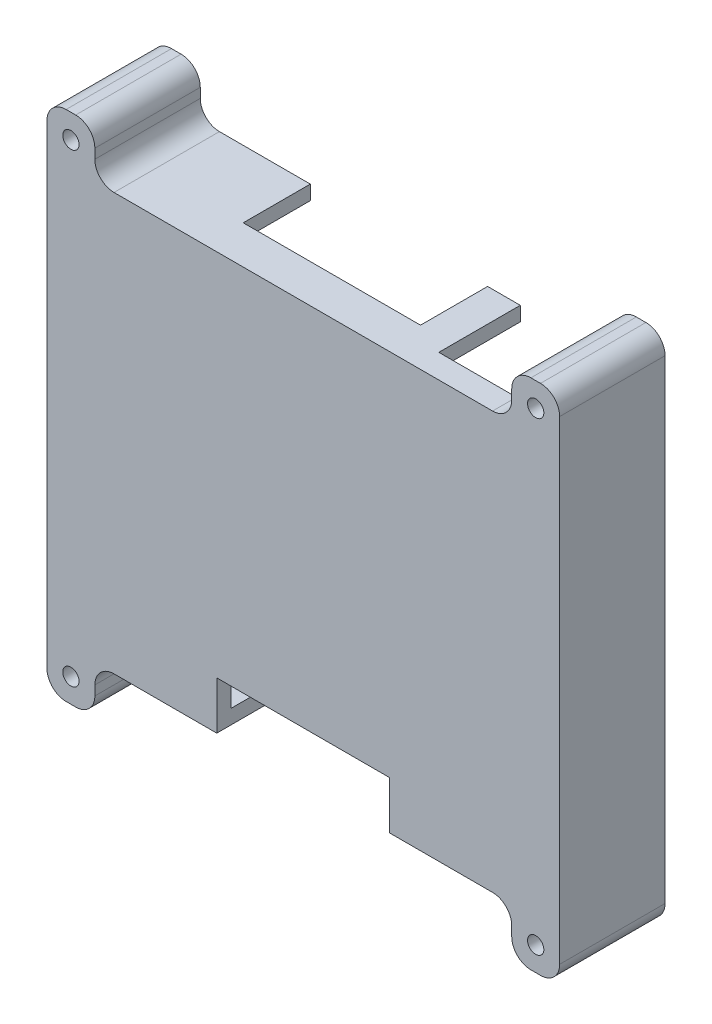
SolidWorks part; units mm, degrees
ref_plane "Płaszczyzna przednia" through (0, 0, 0) normal (0, 0, 1) x (1, 0, 0)
ref_plane "Płaszczyzna górna" through (0, 0, 0) normal (0, 1, 0) x (1, 0, 0)
ref_plane "Płaszczyzna prawa" through (0, 0, 0) normal (1, 0, 0) x (0, 0, -1)
sketch "Sketch1" plane through (0, 0, 0) normal (0, 0, 1) x (1, 0, 0)
  line L1 (-53.5, 43.5) -> (53.5, 43.5)
  line L2 (-53.5, 43.5) -> (-53.5, -43.5)
  line L3 (-53.5, -43.5) -> (53.5, -43.5)
  line L4 (53.5, 43.5) -> (53.5, -43.5)
  line L5 (0, -43.5) -> (0, 43.5) construction
  line L6 (-53.5, 0) -> (53.5, 0) construction
  point P92 (0, 0)
  dimension "D1" = 107
  dimension "D2" = 87
extrude "Boss-Extrude1" add sketch "Sketch1" along normal blind 22
sketch "Sketch2" plane through (0, 0, 0) normal (0, 0, -1) x (-1, 0, 0)
  line L1 (-53.5, -43.5) -> (-43.5, -43.5)
  line L2 (-53.5, -43.5) -> (-53.5, -53.5)
  line L3 (-53.5, -53.5) -> (-43.5, -53.5)
  line L4 (-43.5, -43.5) -> (-43.5, -53.5)
  line L5 (-48.5, -53.5) -> (-48.5, -43.5) construction
  line L6 (-53.5, -48.5) -> (-43.5, -48.5) construction
  point P252 (-48.5, -48.5)
  dimension "D1" = 10
  dimension "D2" = 10
extrude "Boss-Extrude2" add sketch "Sketch2" against normal up to surface (22 mm away) up to face at (0, 0, 22)
mirror "Mirror1" about plane through (0, 0, 0) normal (0, 1, 0) of "Boss-Extrude2" second plane through (0, 0, 0) second plane normal (1, 0, 0)
sketch "Sketch3" plane through (0, 0, 0) normal (0, 0, -1) x (-1, 0, 0)
  line L0 (-43.5, 43.5) -> (43.5, 43.5) construction
  line L1 (-50.5, 40.5) -> (50.5, 40.5)
  line L2 (-50.5, 40.5) -> (-50.5, -40.5)
  line L3 (-50.5, -40.5) -> (50.5, -40.5)
  line L4 (50.5, 40.5) -> (50.5, -40.5)
  line L5 (0, -40.5) -> (0, 40.5) construction
  line L6 (-50.5, 0) -> (50.5, 0) construction
  line L7 (-53.5, -53.5) -> (-53.5, 53.5) construction
  point P200 (0, 0)
  dimension "D1" = 3
  dimension "D2" = 3
extrude "Cut-Extrude1" cut sketch "Sketch3" against normal offset from surface (19 mm away) 3 up to face at (0, 0, 22)
sketch "Sketch4" plane through (0, 0, 22) normal (0, 0, 1) x (1, 0, 0)
  line L1 (-53.5, -53.5) -> (-43.5, -53.5)
  line L2 (-53.5, -53.5) -> (-53.5, -43.5)
  line L3 (-53.5, -43.5) -> (-43.5, -43.5)
  line L4 (-43.5, -53.5) -> (-43.5, -43.5)
  line L5 (-48.5, -43.5) -> (-48.5, -53.5) construction
  line L6 (-53.5, -48.5) -> (-43.5, -48.5) construction
  line L7 (0, -55) -> (0, 55) construction
  line L8 (53.5, -43.5) -> (43.5, -43.5)
  line L9 (43.5, -53.5) -> (43.5, -43.5)
  line L10 (53.5, -53.5) -> (43.5, -53.5)
  line L11 (53.5, -53.5) -> (53.5, -43.5)
  line L12 (53.5, -48.5) -> (43.5, -48.5) construction
  line L13 (48.5, -43.5) -> (48.5, -53.5) construction
  line L14 (55, 0) -> (-55, 0) construction
  point P12 (48.5, -48.5)
  point P17 (48.5, 48.5)
  point P18 (-48.5, 48.5)
  point P160 (-48.5, -48.5)
hole_wizard "M3 Clearance Hole1" positions "Sketch4" profile "Sketch5" hole size "M3" standard "DIN" end condition up to next
sketch "Sketch5" plane through (-48.5, -48.5, 22) normal (1, 0, 0) x (0, -1, 0)
  line L0 (0, 0) -> (0, 22)
  line L1 (0, 22) -> (1.7, 22)
  line L2 (1.7, 22) -> (1.7, 0)
  line L5 (1.7, 0) -> (0, 0)
  line L11 (0, -6.35) -> (0, 107.95) construction
  dimension "Thru Hole Dia." = 3.4
  dimension "Thru Hole Depth" = 22
sketch "Sketch6" plane through (0, -43.5, 0) normal (0, -1, 0) x (1, 0, 0)
  line L0 (-43.5, 0) -> (43.5, 0) construction
  line L1 (40.285, 0) -> (24.285, 0)
  line L2 (40.285, 0) -> (40.285, 17)
  line L3 (40.285, 17) -> (24.285, 17)
  line L4 (24.285, 0) -> (24.285, 17)
  line L5 (32.285, 17) -> (32.285, 0) construction
  line L6 (40.285, 8.5) -> (24.285, 8.5) construction
  line L8 (24.735, 14.9914) -> (39.835, 14.9914) construction
  point P8 (32.285, 14.9914)
  point P196 (32.285, 8.5)
  dimension "D1" = 17
  dimension "D2" = 16
  dimension "D3" = 2.0086
extrude "Cut-Extrude2" cut sketch "Sketch6" against normal up to next
sketch "Sketch12" plane through (0, 43.5, 0) normal (0, 1, 0) x (1, 0, 0)
  line L0 (39.285, -17) -> (23.285, -17)
  line L1 (39.285, -17) -> (39.285, 0)
  line L2 (39.285, 0) -> (23.285, 0)
  line L3 (23.285, -17) -> (23.285, 0)
  line L4 (31.285, 0) -> (31.285, -17) construction
  line L5 (39.285, -8.5) -> (23.285, -8.5) construction
  line L6 (43.5, 0) -> (-43.5, 0) construction
  line L7 (23.735, -14.9914) -> (38.835, -14.9914) construction
  point P4 (31.285, -5.5826)
  point P9 (31.285, -8.5)
  point P13 (31.285, -14.9914)
  dimension "D1" = 17
  dimension "D2" = 16
extrude "Cut-Extrude6" cut sketch "Sketch12" against normal up to next
sketch "Sketch8" plane through (0, 43.5, 0) normal (0, 1, 0) x (1, 0, 0)
  line L0 (23.285, 0) -> (-43.5, 0) construction
  line L1 (-20.536, 0) -> (16.464, 0)
  line L2 (-20.536, 0) -> (-20.536, -14)
  line L3 (-20.536, -14) -> (16.464, -14)
  line L4 (16.464, 0) -> (16.464, -14)
  line L5 (-2.036, -14) -> (-2.036, 0) construction
  line L6 (-20.536, -7) -> (16.464, -7) construction
  line L7 (-0.131, -1.5914) -> (1.139, -1.5914) construction
  line L8 (-3.941, -1.5914) -> (-0.131, -1.5914) construction
  line L9 (-5.211, -1.5914) -> (-3.941, -1.5914) construction
  line L10 (-0.131, -1.5914) -> (1.139, -1.5914) construction
  line L11 (-5.211, -1.5914) -> (-3.941, -1.5914) construction
  point P11 (-0.131, -1.5914)
  point P12 (-3.941, -1.5914)
  point P13 (-2.036, -1.5914)
  point P60 (-2.036, -7)
  dimension "D1" = 37
  dimension "D2" = 14
  dimension "D3" = 1.27
extrude "Cut-Extrude3" cut sketch "Sketch8" against normal up to next
sketch "Sketch9" plane through (0, 0, 22) normal (0, 0, 1) x (1, 0, 0)
  line L0 (-43.5, -43.5) -> (43.5, -43.5) construction
  line L1 (17.9441, -43.5) -> (-18.0559, -43.5)
  line L2 (17.9441, -43.5) -> (17.9441, -33.5)
  line L3 (17.9441, -33.5) -> (-18.0559, -33.5)
  line L4 (-18.0559, -43.5) -> (-18.0559, -33.5)
  line L5 (-0.0559, -33.5) -> (-0.0559, -43.5) construction
  line L6 (17.9441, -38.5) -> (-18.0559, -38.5) construction
  line L8 (15.1941, -33.8779) -> (-15.3059, -33.8779) construction
  point P6 (-0.0559, -33.8779)
  point P128 (-0.0559, -38.5)
  dimension "D1" = 10
  dimension "D2" = 36
extrude "Cut-Extrude4" cut sketch "Sketch9" against normal up to next
fillet "Fillet1" radius 4 13 edges at (40.285, -43.5, 8.5) (43.5, -53.5, 11) (43.5, -43.5, 11) (53.5, -53.5, 11) (-53.5, -53.5, 11) (-43.5, -53.5, 11) (-43.5, -43.5, 11) (53.5, 53.5, 11) (43.5, 53.5, 11) (43.5, 43.5, 11) (-43.5, 53.5, 11) (-43.5, 43.5, 11) (-53.5, 53.5, 11)
sketch "Sketch11" plane through (0, -43.5, 0) normal (0, -1, 0) x (1, 0, 0)
  line L1 (-24.25, 0) -> (-40.25, 0)
  line L2 (-24.25, 0) -> (-24.25, 2)
  line L3 (-24.25, 2) -> (-40.25, 2)
  line L4 (-40.25, 0) -> (-40.25, 2)
  line L5 (-32.25, 2) -> (-32.25, 0) construction
  line L6 (-24.25, 1) -> (-40.25, 1) construction
  line L7 (-40.25, 0) -> (-40.25, -5) construction
  line L8 (-24.25, -5) -> (-24.25, 0) construction
  line L9 (-39.5, 0) -> (-18.0559, 0) construction
  point P272 (-32.25, 1)
  dimension "D1" = 2
extrude "Cut-Extrude5" cut sketch "Sketch11" against normal up to next and the other way through all
